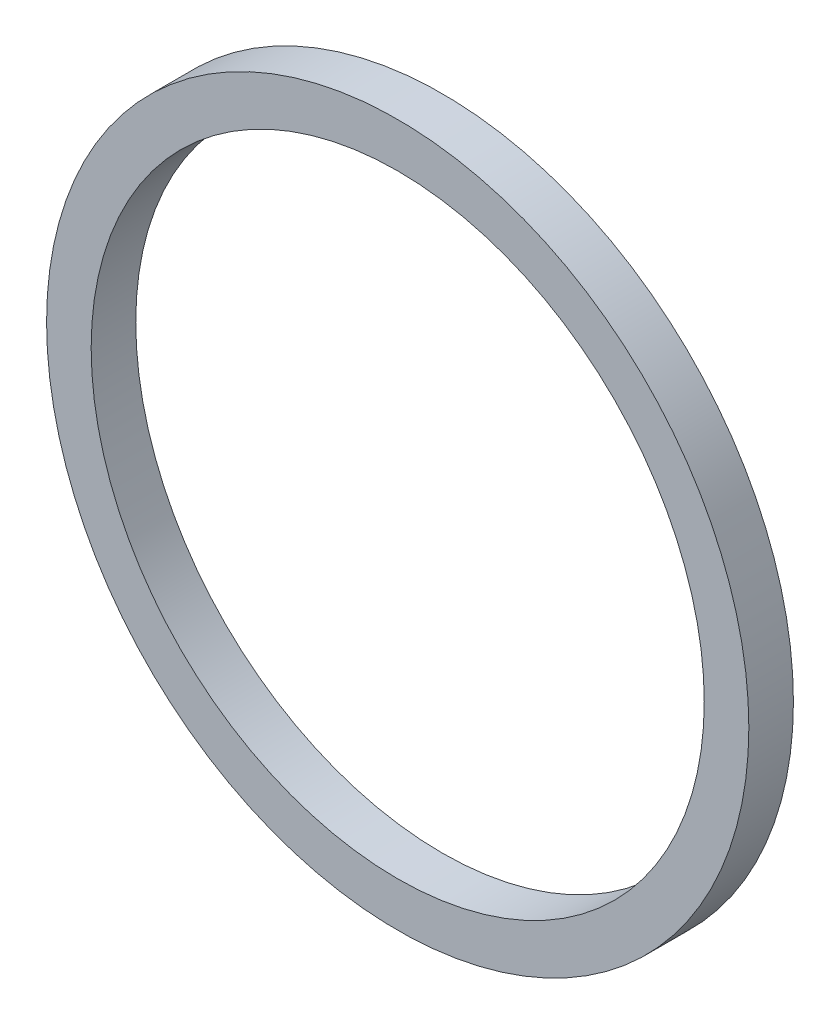
SolidWorks part; units mm, degrees
ref_plane "前视基准面" through (0, 0, 0) normal (0, 0, 1) x (1, 0, 0)
ref_plane "上视基准面" through (0, 0, 0) normal (0, 1, 0) x (1, 0, 0)
ref_plane "右视基准面" through (0, 0, 0) normal (1, 0, 0) x (0, 0, -1)
sketch "草图1" plane through (0, 0, 0) normal (0, 0, 1) x (1, 0, 0)
  circle A0 centre (0, 0) radius 55
  circle A1 centre (0, 0) radius 63
  dimension "D1" = 110
  dimension "D2" = 126
extrude "凸台-拉伸1" add sketch "草图1" along normal blind 8
